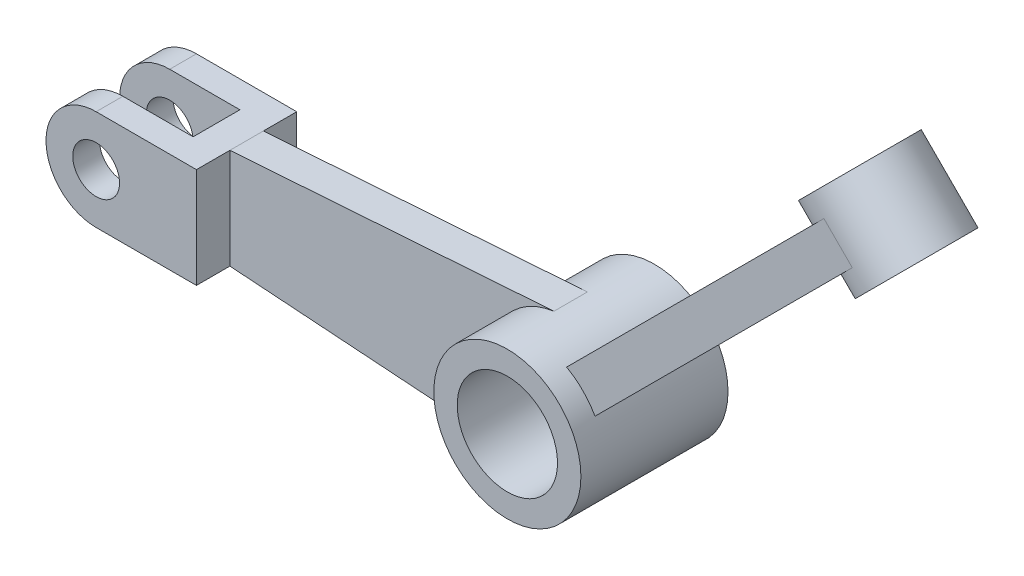
SolidWorks part; units mm, degrees
ref_plane "Plano frontal" through (0, 0, 0) normal (0, 0, 1) x (1, 0, 0)
ref_plane "Plano superior" through (0, 0, 0) normal (0, 1, 0) x (1, 0, 0)
ref_plane "Plano direito" through (0, 0, 0) normal (1, 0, 0) x (0, 0, -1)
sketch "Esboço1" plane through (0, 0, 0) normal (0, 0, 1) x (1, 0, 0)
  line L0 (0, 0) -> (-65, 0) construction
  line L2 (-65, 7.5) -> (-50, 7.5)
  line L4 (-65, -7.5) -> (-50, -7.5)
  line L5 (-50, 7.5) -> (-50, -7.5)
  arc A2 (-65, 7.5) -> (-65, -7.5) centre (-65, 0) ccw
  dimension "D1" = 15
  dimension "D2" = 15
  dimension "D3" = 15
  dimension "D4" = 65
extrude "Ressalto-extrusão1" add sketch "Esboço1" along normal mid plane 15
sketch "Esboço2" plane through (0, 0, 0) normal (0, 0, 1) x (1, 0, 0)
  circle A0 centre (0, 0) radius 11
  dimension "D1" = 22
extrude "Ressalto-extrusão2" add sketch "Esboço2" along normal mid plane 22 separate body
sketch "Esboço3" plane through (0, 0, 0) normal (0, 0, 1) x (1, 0, 0)
  line L0 (-50, 7.5) -> (0, 11)
  line L1 (0, 11) -> (0, -11)
  line L2 (0, -11) -> (-50, -7.5)
  line L3 (-50, -7.5) -> (-50, 7.5)
  circle A0 centre (0, 0) radius 11 construction
extrude "Ressalto-extrusão4" add sketch "Esboço3" along normal mid plane 5 contours L2 L3 L0 L1
sketch "Esboço4" plane through (0, 0, 0) normal (0, 0, 1) x (1, 0, 0)
  line L0 (0, 0) -> (34.8976, 0) construction
  line L1 (0, 0) -> (45.9619, 45.9619) construction
  line L2 (2.1213, -2.1213) -> (48.0833, 43.8406)
  line L3 (-2.1213, 2.1213) -> (43.8406, 48.0833)
  line L4 (43.8406, 48.0833) -> (48.0833, 43.8406)
  line L5 (-2.1213, 2.1213) -> (2.1213, -2.1213)
  dimension "D1" = 45
  dimension "D4" = 65
  dimension "D2" = 3
  dimension "D3" = 3
extrude "Ressalto-extrusão5" add sketch "Esboço4" along normal mid plane 15
ref_plane "Plano1" through (0, 0, 0) normal (-0.7071, 0.7071, 0) x (0, 0, 1)
sketch "Esboço5" plane through (0, 0, 0) normal (-0.7071, 0.7071, 0) x (0, 0, 1)
  line L0 (7.5, 65) -> (-7.5, 65) construction
  circle A0 centre (0, 65) radius 7.5
extrude "Ressalto-extrusão6" add sketch "Esboço5" along normal mid plane 12
sketch "Esboço6" plane through (0, 7.5, 0) normal (0, 1, 0) x (1, 0, 0)
  line L0 (-65, -7.5) -> (-65, 7.5) construction
  line L1 (-54.5, 3.5) -> (-75.5, 3.5)
  line L2 (-54.5, 3.5) -> (-54.5, -3.5)
  line L3 (-54.5, -3.5) -> (-75.5, -3.5)
  line L4 (-75.5, 3.5) -> (-75.5, -3.5)
  line L5 (-54.5, 3.5) -> (-75.5, -3.5) construction
  line L6 (-54.5, -3.5) -> (-75.5, 3.5) construction
  line L7 (-72.5, 7.5) -> (-72.5, -7.5) construction
  line L8 (-65, 7.5) -> (-72.5, 7.5) construction
  line L11 (-72.5, -7.5) -> (-65, -7.5) construction
  point P0 (-65, 0)
  dimension "D1" = 18
  dimension "D2" = 4
  dimension "D3" = 4
extrude "Corte-extrusão1" cut sketch "Esboço6" against normal through all
sketch "Esboço7" plane through (0, 0, 0) normal (0, 0, 1) x (1, 0, 0)
  circle A0 centre (-65, 0) radius 3.5
  dimension "D1" = 7
extrude "Corte-extrusão3" cut sketch "Esboço7" against normal through all both and the other way through all
sketch "Esboço8" plane through (0, 0, 0) normal (0, 0, 1) x (1, 0, 0)
  circle A0 centre (0, 0) radius 7.5
  dimension "D1" = 15
extrude "Corte-extrusão5" cut sketch "Esboço8" against normal through all both and the other way through all
sketch "Esboço9" plane through (-4.2426, 4.2426, 0) normal (-0.7071, 0.7071, 0) x (0, 0, 1)
  circle A0 centre (0, 65) radius 3.5
  dimension "D1" = 7
extrude "Corte-extrusão6" cut sketch "Esboço9" against normal through all both
